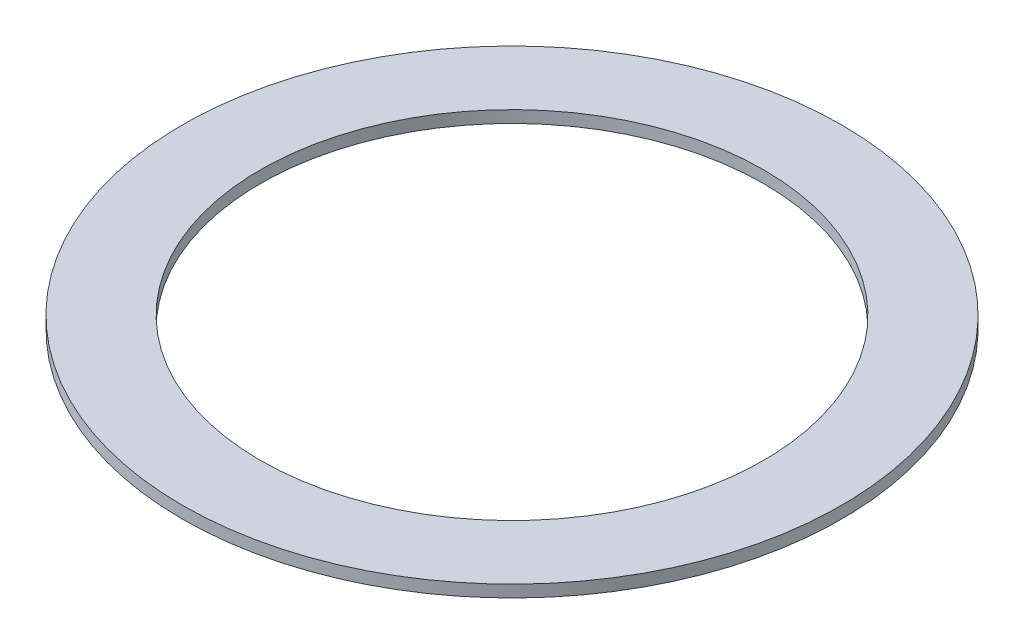
SolidWorks part; units mm, degrees
ref_plane "Front Plane" through (0, 0, 0) normal (0, 0, 1) x (1, 0, 0)
ref_plane "Top Plane" through (0, 0, 0) normal (0, 1, 0) x (1, 0, 0)
ref_plane "Right Plane" through (0, 0, 0) normal (1, 0, 0) x (0, 0, -1)
sketch "Sketch1" plane through (0, 0, 0) normal (0, 1, 0) x (1, 0, 0)
  circle A0 centre (0, 0) radius 21
  circle A1 centre (0, 0) radius 27.5
  dimension "D1" = 55
  dimension "D2" = 42
extrude "Boss-Extrude1" add sketch "Sketch1" along normal blind 1 contours A1 | A0
